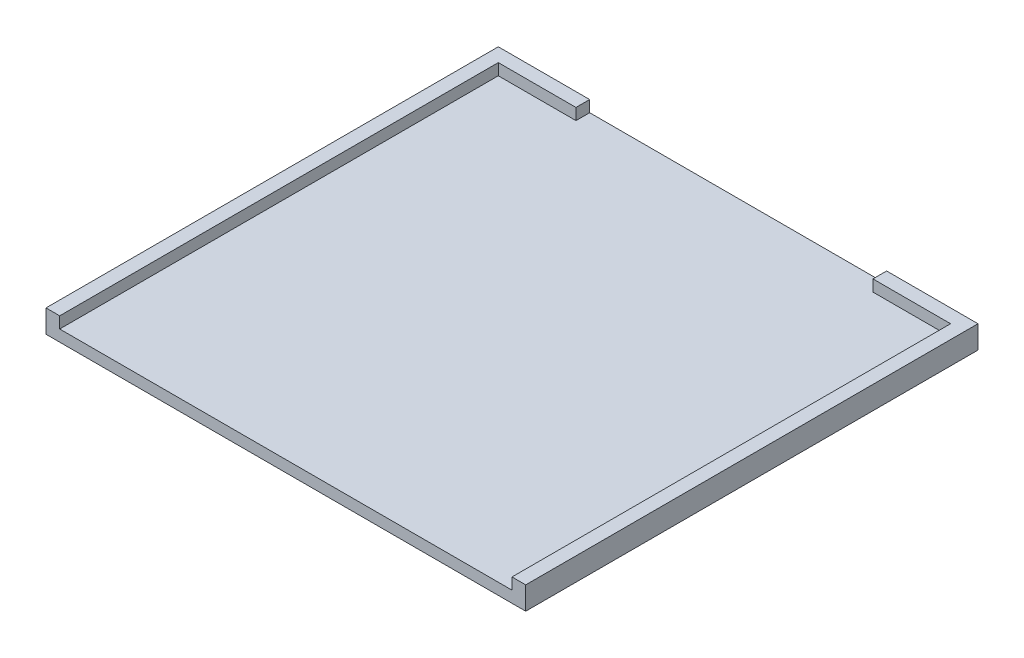
SolidWorks part; units mm, degrees
ref_plane "Front Plane" through (0, 0, 0) normal (0, 0, 1) x (1, 0, 0)
ref_plane "Top Plane" through (0, 0, 0) normal (0, 1, 0) x (1, 0, 0)
ref_plane "Right Plane" through (0, 0, 0) normal (1, 0, 0) x (0, 0, -1)
sketch "Sketch1" plane through (0, 0, 0) normal (0, 1, 0) x (1, 0, 0)
  line L0 (-15.1184, 7.3428) -> (-15.1184, -12.4572)
  line L1 (-14.5184, 6.7428) -> (5.2816, 6.7428)
  line L2 (-14.5184, 6.7428) -> (-14.5184, -12.4572)
  line L4 (5.2816, 6.7428) -> (5.2816, -12.4572)
  line L6 (5.8816, 7.3428) -> (5.8816, -12.4572)
  line L7 (-15.1184, 7.3428) -> (5.8816, 7.3428)
  line L8 (-14.5184, -12.4572) -> (-15.1184, -12.4572)
  line L9 (5.2816, -12.4572) -> (5.8816, -12.4572)
  line L11 (-15.1184, -13.0572) -> (5.8816, -13.0572) construction
  line L12 (-15.1184, 7.3428) -> (-15.1184, -13.0572) construction
  line L13 (-14.5184, -12.4572) -> (5.2816, -12.4572) construction
  line L14 (5.8816, 7.3428) -> (5.8816, -13.0572) construction
  dimension "D1" = 19.8
  dimension "D2" = 19.2
  dimension "D3" = 0.6
extrude "Boss-Extrude1" add sketch "Sketch1" along normal blind 0.5
sketch "Sketch2" plane through (0, 0, 0) normal (0, -1, 0) x (1, 0, 0)
  line L0 (5.8816, 12.4572) -> (5.8816, -7.3428)
  line L1 (5.8816, -7.3428) -> (-15.1184, -7.3428)
  line L2 (-15.1184, -7.3428) -> (-15.1184, 12.4572)
  line L3 (-15.1184, 12.4572) -> (5.8816, 12.4572)
extrude "Boss-Extrude2" add sketch "Sketch2" along normal blind 0.5
sketch "Sketch3" plane through (0, 0, -6.7428) normal (0, 0, 1) x (1, 0, 0)
  line L0 (-4.6184, 0.5) -> (-4.6184, 0) construction
  line L1 (-14.5184, 0.5) -> (5.2816, 0.5) construction
  line L2 (-14.5184, 0) -> (5.2816, 0) construction
  line L4 (-11.1184, 0.5) -> (1.8816, 0.5)
  line L5 (-11.1184, 0.5) -> (-11.1184, 0)
  line L6 (-11.1184, 0) -> (1.8816, 0)
  line L7 (1.8816, 0.5) -> (1.8816, 0)
  dimension "D1" = 13
extrude "Cut-Extrude1" cut sketch "Sketch3" against normal through all
